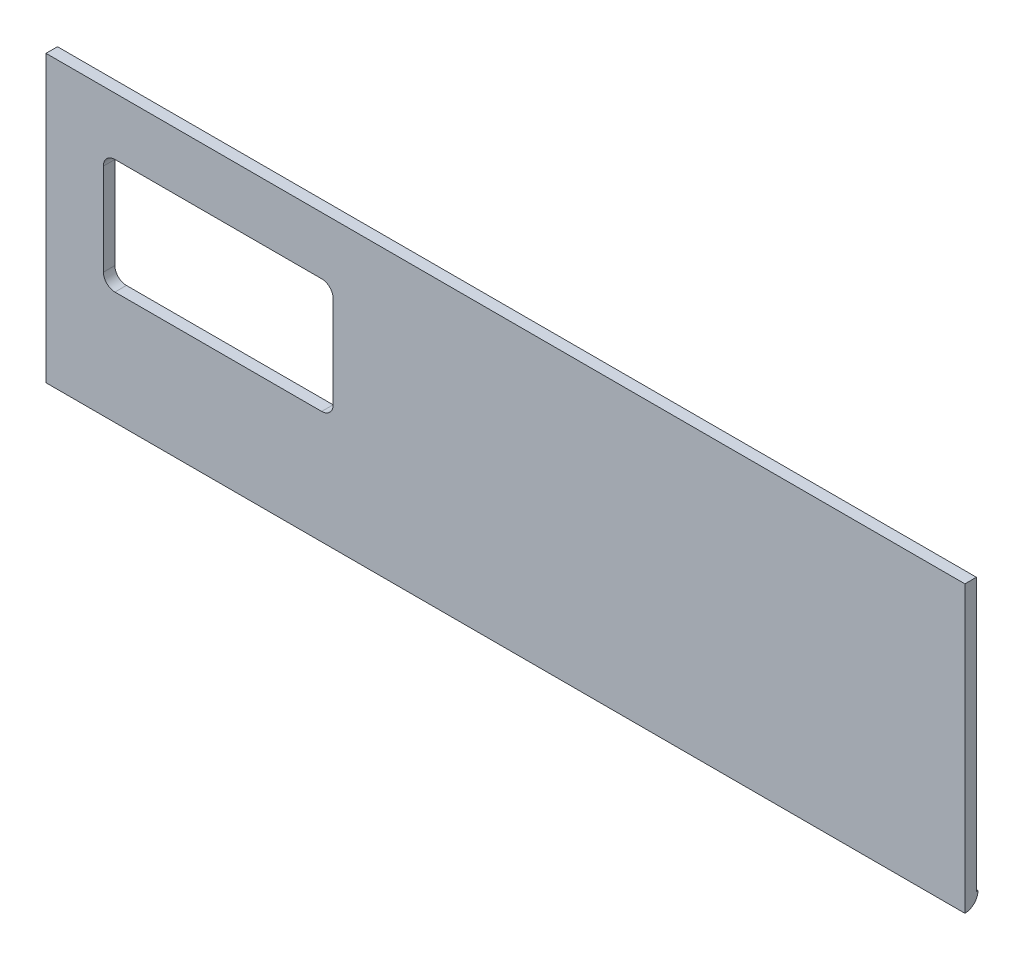
SolidWorks part; units mm, degrees
ref_plane "Front Plane" through (0, 0, 0) normal (0, 0, 1) x (1, 0, 0)
ref_plane "Top Plane" through (0, 0, 0) normal (0, 1, 0) x (1, 0, 0)
ref_plane "Right Plane" through (0, 0, 0) normal (1, 0, 0) x (0, 0, -1)
sketch "Sketch1" plane through (0, 0, 0) normal (0, 0, 1) x (1, 0, 0)
  line L0 (-40, 0) -> (0, 0) construction
  line L1 (-40, 12.35) -> (40, 12.35)
  line L2 (-40, 12.35) -> (-40, -12.35)
  line L3 (-40, -12.35) -> (40, -12.35)
  line L4 (40, 12.35) -> (40, -12.35)
  line L5 (0, 0) -> (0, -12.35) construction
  dimension "D1" = 80
  dimension "D2" = 24.7
extrude "Boss-Extrude1" add sketch "Sketch1" along normal blind 1
sketch "Sketch2" plane through (-40, 0, 0) normal (-1, 0, 0) x (0, 0, 1)
  line L0 (0, -12.35) -> (1, -12.35)
  line L3 (0, -12.35) -> (0, -11.35)
  line L4 (0, 12.35) -> (0, -12.35) construction
  arc A1 (0, -11.35) -> (1, -12.35) centre (1, -11.35) ccw
extrude "Cut-Extrude1" cut sketch "Sketch2" against normal blind 100
sketch "Sketch3" plane through (0, 0, 0) normal (0, 0, -1) x (-1, 0, 0)
  line L0 (-40, 12.35) -> (40, 12.35) construction
  line L1 (34, 7.35) -> (16, 7.35)
  line L2 (35, 6.35) -> (35, -1.65)
  line L3 (34, -2.65) -> (16, -2.65)
  line L4 (15, 6.35) -> (15, -1.65)
  line L5 (40, 12.35) -> (40, -11.35) construction
  arc A0 (16, 7.35) -> (15, 6.35) centre (16, 6.35) ccw
  arc A1 (35, -1.65) -> (34, -2.65) centre (34, -1.65) cw
  arc A2 (16, -2.65) -> (15, -1.65) centre (16, -1.65) cw
  arc A3 (34, 7.35) -> (35, 6.35) centre (34, 6.35) cw
  point P10 (15, 7.35)
  point P13 (35, -2.65)
  point P18 (35, 7.35)
  dimension "D5" = 1
  dimension "D1" = 5
  dimension "D2" = 5
  dimension "D3" = 20
  dimension "D4" = 10
extrude "Cut-Extrude2" cut sketch "Sketch3" against normal up to surface (1 mm away) up to face at (0, 0, 1)
sketch "Sketch4" plane through (40, 0, 0) normal (1, 0, 0) x (0, 0, -1)
  line L0 (0, -11.35) -> (0, 12.35) construction
  line L1 (-1, -12.49) -> (-1, -12.35)
  line L2 (0, -11.35) -> (0.14, -11.35)
  arc A0 (-1, -12.35) -> (0, -11.35) centre (-1, -11.35) ccw
  arc A1 (-1, -12.35) -> (0, -11.35) centre (-1, -11.35) ccw construction
  arc A2 (-1, -12.49) -> (0.14, -11.35) centre (-1, -11.35) ccw
  dimension "D1" = 0.14
  dimension "D2" = 0.14
extrude "Boss-Extrude2" add sketch "Sketch4" against normal up to surface (80 mm away) up to face at (-40, 0.1982, 0.4482)
